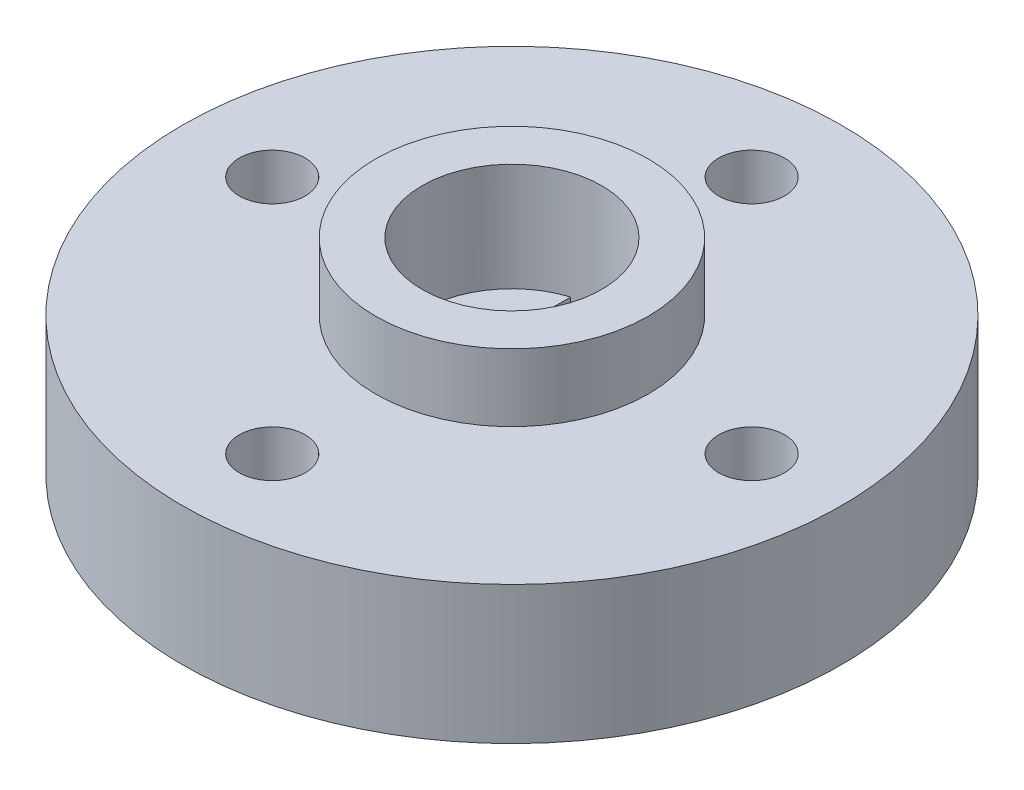
SolidWorks part; units mm, degrees
ref_plane "Front Plane" through (0, 0, 0) normal (0, 0, 1) x (1, 0, 0)
ref_plane "Top Plane" through (0, 0, 0) normal (0, 1, 0) x (1, 0, 0)
ref_plane "Right Plane" through (0, 0, 0) normal (1, 0, 0) x (0, 0, -1)
sketch "Sketch3" plane through (0, 0, 0) normal (0, 0, 1) x (1, 0, 0)
  line L0 (2.85, 0) -> (11, 0)
  line L1 (55, 0) -> (-55, 0) construction
  line L2 (11, 0) -> (11, 4.6)
  line L3 (11, 4.6) -> (4.55, 4.6)
  line L4 (4.55, 4.6) -> (4.55, 6.85)
  line L5 (4.55, 6.85) -> (3, 6.85)
  line L6 (3, 6.85) -> (3, 3.25)
  line L7 (3, 3.25) -> (0, 3.25)
  line L8 (0, -55) -> (0, 55) construction
  line L9 (0, 3.25) -> (0, 1.6)
  line L13 (0, 1.6) -> (2.85, 1.6)
  line L14 (2.85, 0) -> (2.85, 1.6)
  dimension "D1" = 2.85
  dimension "D2" = 4.6
  dimension "D3" = 6.85
  dimension "D4" = 4.55
  dimension "D5" = 3
  dimension "D6" = 3.6
  dimension "D7" = 1.6
  dimension "D8" = 11
revolve "Revolve1" add sketch "Sketch3" angle 360 about L9
sketch "Sketch4" plane through (0, 3.25, 0) normal (0, 1, 0) x (1, 0, 0)
  line L2 (-0.9, 2.8618) -> (-0.9, 0.8675)
  line L4 (0.9, 2.8618) -> (0.9, 0.8675)
  line L5 (0, -3.7675) -> (0, 3.7675) construction
  arc A0 (-0.9, 0.8675) -> (0.9, 0.8675) centre (0, 0) ccw
  circle A1 centre (0, 0) radius 3 construction
  arc A2 (0.9, 2.8618) -> (-0.9, 2.8618) centre (0, 0) ccw
  point P3 (0, 3)
  dimension "D1" = 1.25
  dimension "D2" = 1.8
extrude "Cut-Extrude1" cut sketch "Sketch4" against normal through all both and the other way through all
sketch "Sketch5" plane through (0, 0, 0) normal (0, -1, 0) x (1, 0, 0)
  line L0 (0, -3.7675) -> (0, 3.7675) construction
  line L1 (3.7675, 0) -> (-3.7675, 0) construction
  circle A0 centre (0, 8) radius 1.1
  circle A1 centre (8, 0) radius 1.1
  circle A2 centre (0, -8) radius 1.1
  circle A3 centre (-8, 0) radius 1.1
  point P15 (0, 0)
  dimension "D2" = 2.2
  dimension "D1" = 8
  dimension "D3" = 4
extrude "Cut-Extrude2" cut sketch "Sketch5" against normal blind 10
